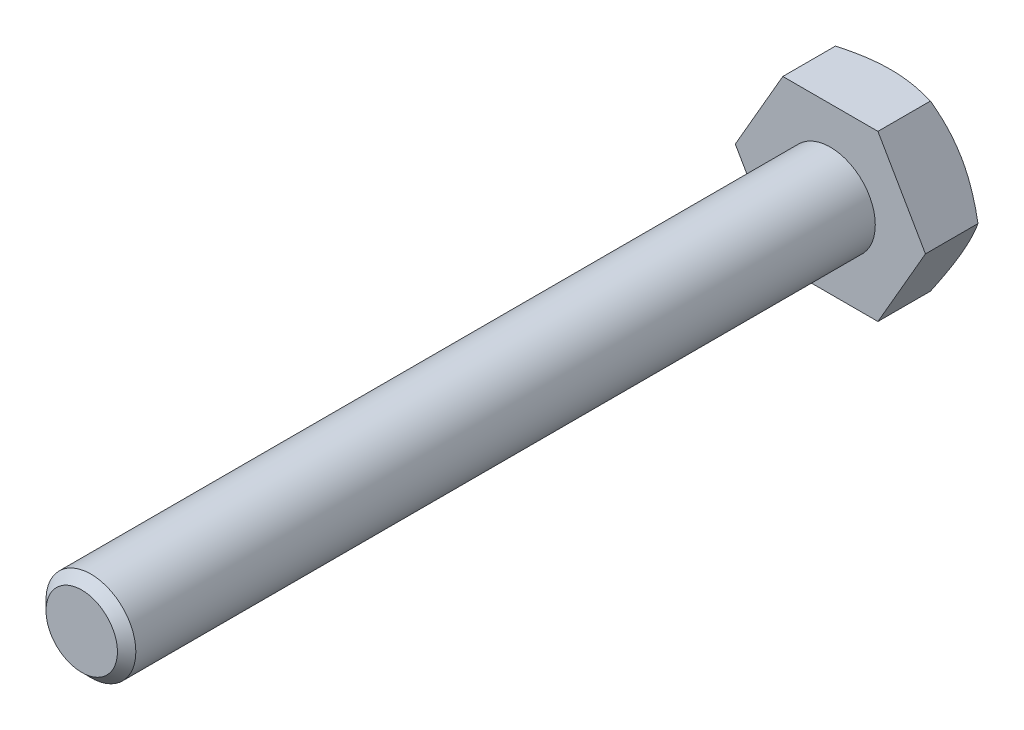
SolidWorks part; units mm, degrees
material "Plain Carbon Steel"
ref_plane "Front Plane" through (0, 0, 0) normal (0, 0, 1) x (1, 0, 0)
ref_plane "Top Plane" through (0, 0, 0) normal (0, 1, 0) x (1, 0, 0)
ref_plane "Right Plane" through (0, 0, 0) normal (1, 0, 0) x (0, 0, -1)
sketch "Sketch1" plane through (0, 0, 0) normal (0, 0, 1) x (1, 0, 0)
  line L1 (3.1754, 0) -> (1.5877, 2.75)
  line L2 (1.5877, 2.75) -> (-1.5877, 2.75)
  line L3 (-1.5877, 2.75) -> (-3.1754, 0)
  line L4 (-3.1754, 0) -> (-1.5877, -2.75)
  line L5 (-1.5877, -2.75) -> (1.5877, -2.75)
  line L6 (1.5877, -2.75) -> (3.1754, 0)
  circle A0 centre (0, 0) radius 2.75 construction
  dimension "D1" = 5.5
extrude "Extrude1" add sketch "Sketch1" along normal blind 2
sketch "Sketch2" plane through (0, 0, 2) normal (0, 0, 1) x (1, 0, 0)
  circle A0 centre (0, 0) radius 1.5
  dimension "D1" = 3
extrude "Extrude2" add sketch "Sketch2" along normal blind 25
cosmetic thread "Cosmetic Thread1" parameters "D2"=2.386
sketch "Sketch3" plane through (0, 0, 0) normal (1, 0, 0) x (0, 0, -1)
  line L0 (0, 2.75) -> (0, 102.75)
  line L1 (0, 102.75) -> (-57.735, 102.75)
  line L2 (-57.735, 102.75) -> (0, 2.75)
  line L3 (0, 0) -> (11.4679, 0) construction
  dimension "D1" = 30
  dimension "D2" = 100
revolve "Cut-Revolve1" cut sketch "Sketch3" angle 360 about L3
chamfer "Chamfer1" distance 0.307 angle 45 1 edges at (1.5, 0, 27)
